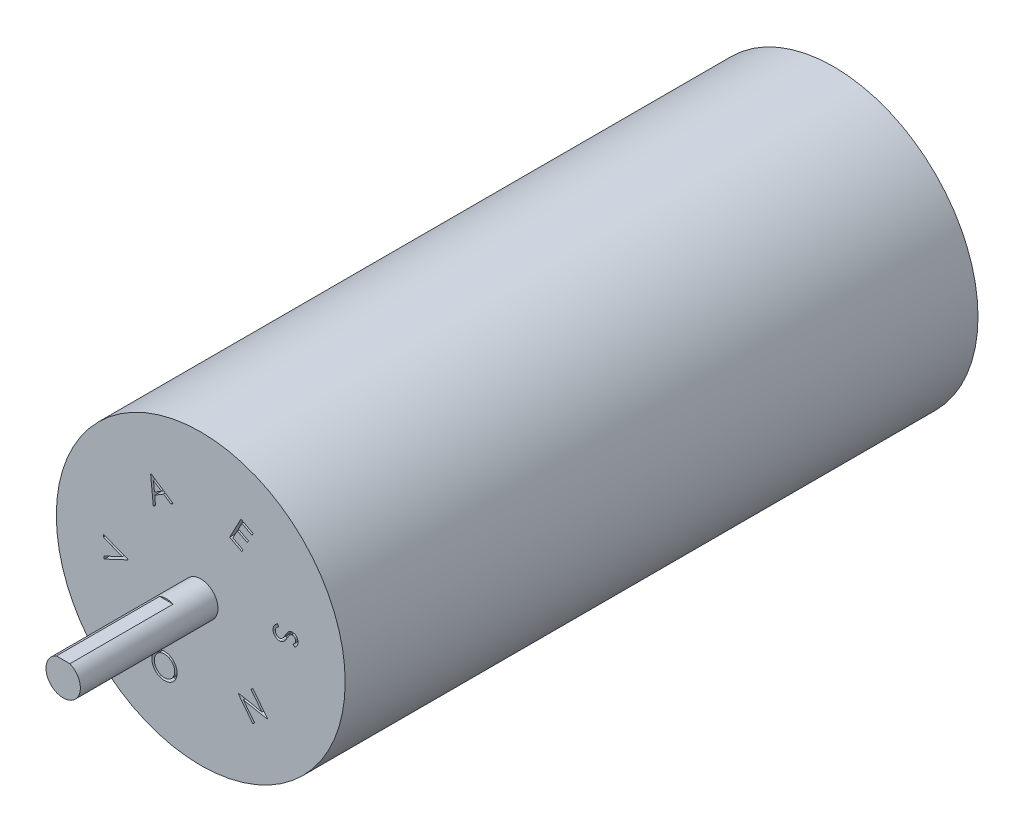
SolidWorks part; units mm, degrees
ref_plane "Plano frontal" through (0, 0, 0) normal (0, 0, 1) x (1, 0, 0)
ref_plane "Plano superior" through (0, 0, 0) normal (0, 1, 0) x (1, 0, 0)
ref_plane "Plano direito" through (0, 0, 0) normal (1, 0, 0) x (0, 0, -1)
sketch "Esboço1" plane through (0, 0, 0) normal (0, 0, 1) x (1, 0, 0)
  circle A0 centre (0, 0) radius 21
  dimension "D1" = 42
extrude "Ressalto-extrusão1" add sketch "Esboço1" along normal blind 92
sketch "Esboço2" plane through (0, 0, 92) normal (0, 0, 1) x (1, 0, 0)
  circle A0 centre (0, 0) radius 2.5
  dimension "D1" = 5
extrude "Ressalto-extrusão2" add sketch "Esboço2" along normal blind 20
sketch "Esboço3" plane through (0, 0, 112) normal (0, 0, 1) x (1, 0, 0)
  line L0 (-0.9798, 2.3) -> (0.9798, 2.3)
  circle A0 centre (0, 0) radius 2.5 construction
  arc A1 (-0.9798, 2.3) -> (0.9798, 2.3) centre (0, 0) cw
  point P7 (0, 2.5)
  dimension "D1" = 0.2
extrude "Corte-extrusão1" cut sketch "Esboço3" against normal blind 15
sketch "Esboço4" plane through (0, 0, 92) normal (0, 0, 1) x (1, 0, 0)
  circle A0 centre (0, 0) radius 10.7521 construction
  text T0 "NOVAES"
extrude "Corte-extrusão2" cut sketch "Esboço4" against normal blind 1
